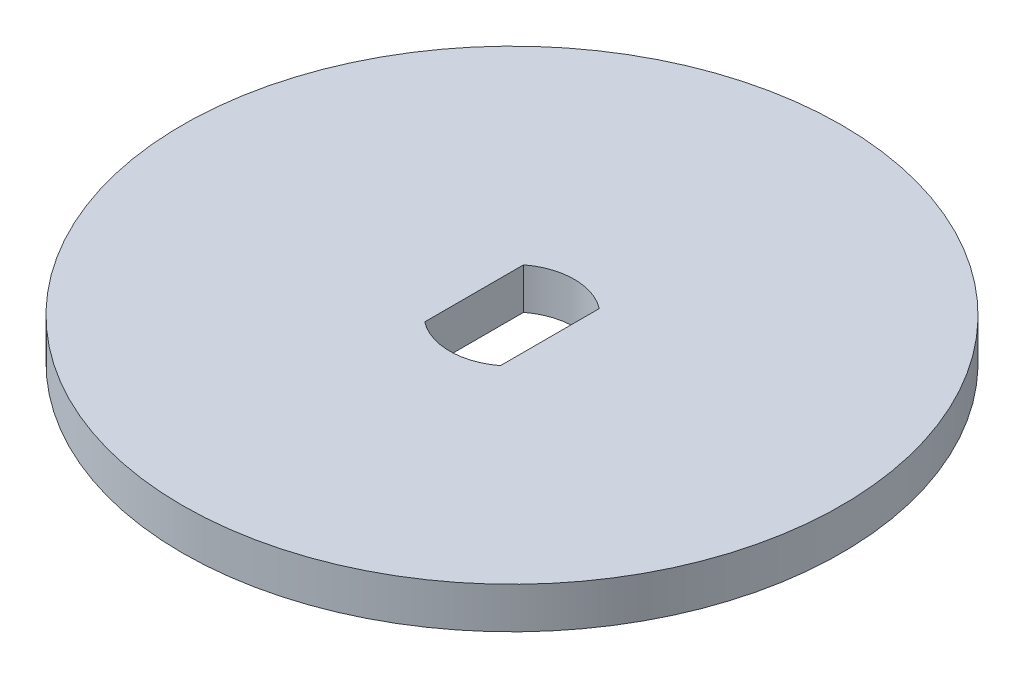
SolidWorks part; units mm, degrees
ref_plane "Front Plane" through (0, 0, 0) normal (0, 0, 1) x (1, 0, 0)
ref_plane "Top Plane" through (0, 0, 0) normal (0, 1, 0) x (1, 0, 0)
ref_plane "Right Plane" through (0, 0, 0) normal (1, 0, 0) x (0, 0, -1)
sketch "Sketch1" plane through (0, 0, 0) normal (0, 1, 0) x (1, 0, 0)
  line L0 (-2.9196, 3.81) -> (-2.9196, -3.81)
  line L1 (2.9196, 3.81) -> (2.9196, -3.81)
  circle A0 centre (0, 0) radius 25.4
  arc A1 (-2.9196, -3.81) -> (2.9196, -3.81) centre (0, 0) ccw
  arc A2 (2.9196, 3.81) -> (-2.9196, 3.81) centre (0, 0) ccw
  dimension "D1" = 50.8
  dimension "D2" = 7.62
extrude "Boss-Extrude1" add sketch "Sketch1" against normal blind 3.175
